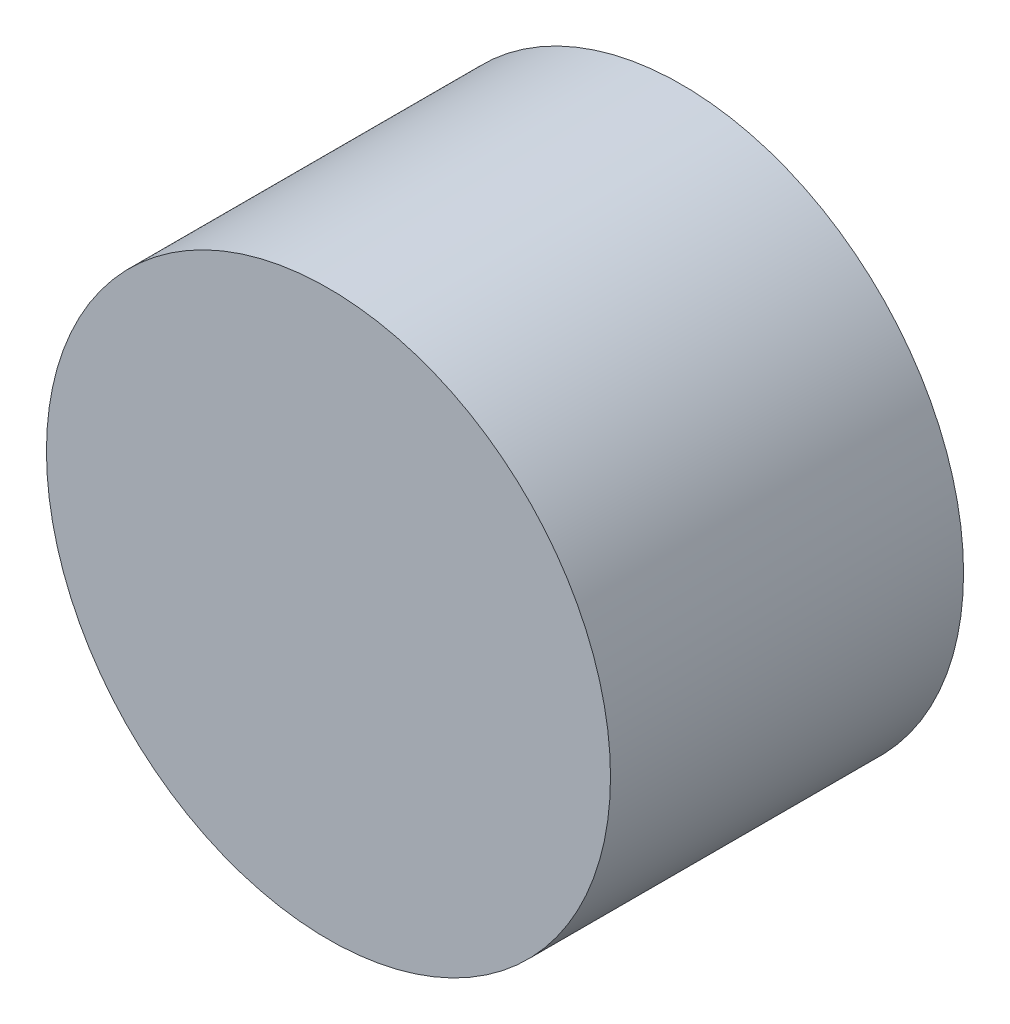
SolidWorks part; units mm, degrees
ref_plane "Ön Düzlem" through (0, 0, 0) normal (0, 0, 1) x (1, 0, 0)
ref_plane "Üst Düzlem" through (0, 0, 0) normal (0, 1, 0) x (1, 0, 0)
ref_plane "Sağ Düzlem" through (0, 0, 0) normal (1, 0, 0) x (0, 0, -1)
sketch "Çizim1" plane through (0, 0, 0) normal (0, 0, 1) x (1, 0, 0)
  circle A0 centre (-19.5881, 18.1476) radius 20.7702
extrude "Yükseklik-Ekstrüzyon1" add sketch "Çizim1" along normal blind 26
